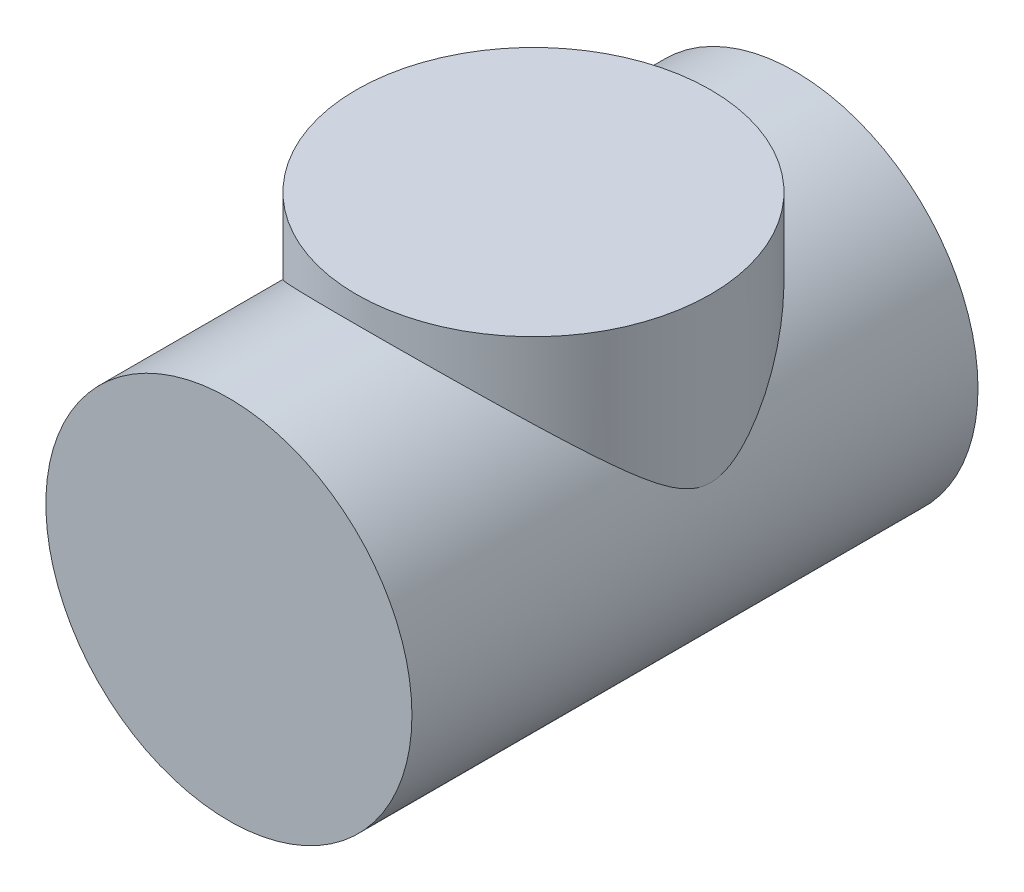
SolidWorks part; units mm, degrees
ref_plane "Front Plane" through (0, 0, 0) normal (0, 0, 1) x (1, 0, 0)
ref_plane "Top Plane" through (0, 0, 0) normal (0, 1, 0) x (1, 0, 0)
ref_plane "Right Plane" through (0, 0, 0) normal (1, 0, 0) x (0, 0, -1)
sketch "Sketch1" plane through (0, 0, 0) normal (0, 0, 1) x (1, 0, 0)
  circle A0 centre (0, 0) radius 0.0595
extrude "Boss-Extrude1" add sketch "Sketch1" along normal blind 0.184 from offset 0.085 offset against normal yes
sketch "Sketch2" plane through (0, 0, 0) normal (0, 1, 0) x (1, 0, 0)
  circle A0 centre (0, 0) radius 0.0576
  point P4 (0, 0)
extrude "Boss-Extrude2" add sketch "Sketch2" along normal blind 0.068
